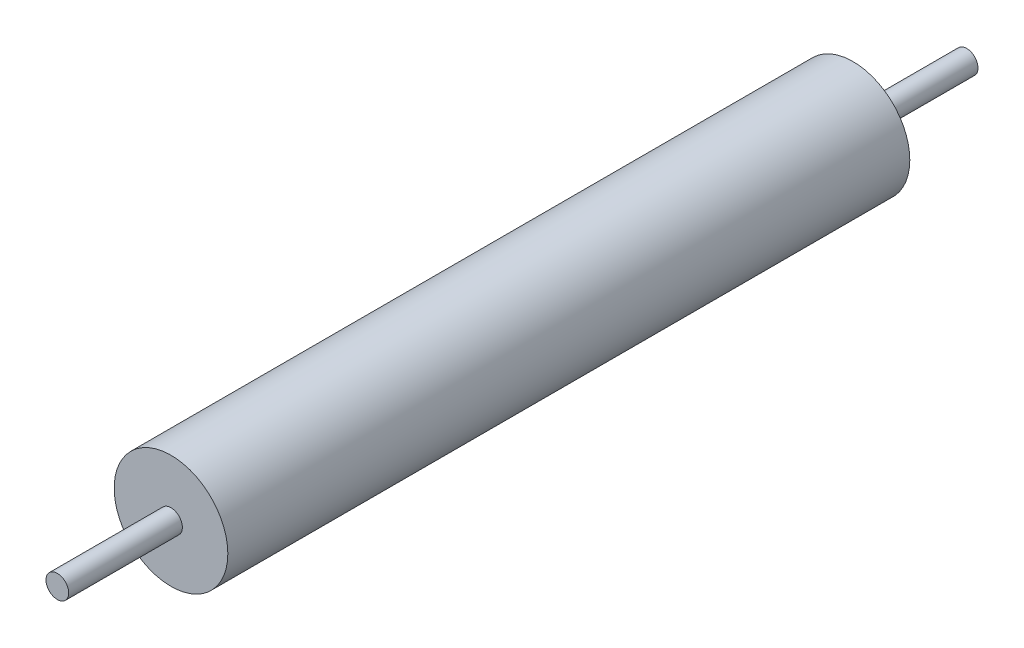
SolidWorks part; units mm, degrees
ref_plane "前视基准面" through (0, 0, 0) normal (0, 0, 1) x (1, 0, 0)
ref_plane "上视基准面" through (0, 0, 0) normal (0, 1, 0) x (1, 0, 0)
ref_plane "右视基准面" through (0, 0, 0) normal (1, 0, 0) x (0, 0, -1)
sketch "草图1" plane through (0, 0, 0) normal (0, 0, 1) x (1, 0, 0)
  circle A0 centre (0, 0) radius 2.5
  dimension "D1" = 5
extrude "凸台-拉伸1" add sketch "草图1" along normal mid plane 200
sketch "草图3" plane through (0, 0, 0) normal (0, 0, 1) x (1, 0, 0)
  circle A0 centre (0, 0) radius 12.5
  dimension "D1" = 25
extrude "凸台-拉伸2" add sketch "草图3" along normal mid plane 150
